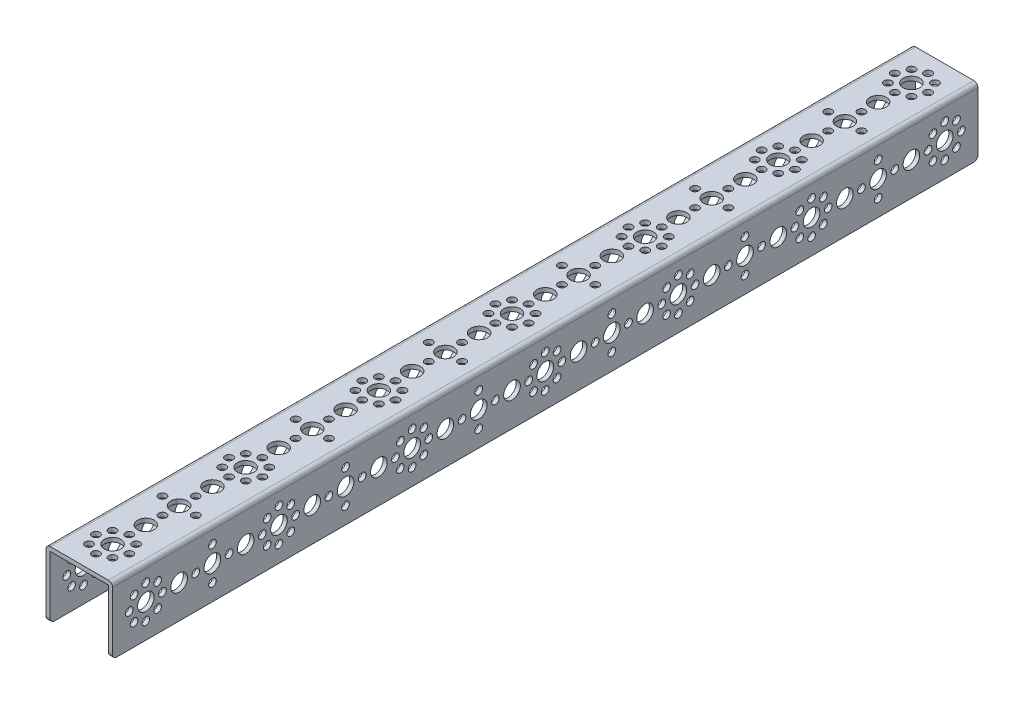
SolidWorks part; units mm, degrees
ref_plane "Front Plane" through (0, 0, 0) normal (0, 0, 1) x (1, 0, 0)
ref_plane "Top Plane" through (0, 0, 0) normal (0, 1, 0) x (1, 0, 0)
ref_plane "Right Plane" through (0, 0, 0) normal (1, 0, 0) x (0, 0, -1)
ref_plane "Plane1" through (-16, 0, 0) normal (-1, 0, 0) x (0, -1, 0)
sketch "Sketch1" plane through (-16, 0, 0) normal (-1, 0, 0) x (0, -1, 0)
  line L0 (16, 0) -> (-16, 0)
  line L1 (-16, 0) -> (-16, -416)
  line L2 (-16, -416) -> (16, -416)
  line L3 (16, -416) -> (16, 0)
extrude "Boss-Extrude1" add sketch "Sketch1" against normal blind 32
sketch "Sketch2" plane through (0, 0, 0) normal (0, 0, 1) x (1, 0, 0)
  line L0 (-14, -16) -> (14, -16)
  line L1 (14, -16) -> (14, 14)
  line L2 (14, 14) -> (-14, 14)
  line L3 (-14, 14) -> (-14, -16)
extrude "Cut-Extrude1" cut sketch "Sketch2" against normal through all
hole_wizard "Ø8.0 (8) Diameter Hole1" positions "Sketch4" profile "Sketch3" hole size "Ø8.0" standard "ANSI Metric"
sketch "Sketch4" plane through (14, 0, 0) normal (-1, 0, 0) x (0, 0, 1)
  point P0 (-80, 0)
  point P1 (-112, 0)
  point P2 (-16, 0)
  point P3 (-48, 0)
  point P4 (-128, 0)
  point P5 (-96, 0.1754)
  point P6 (-64, 0)
  point P7 (-32, 0)
  point P8 (-272, 0)
  point P9 (-336, 0)
  point P10 (-304, 0)
  point P11 (-400, 0)
  point P12 (-368, 0)
  point P13 (-288, 0)
  point P14 (-320, -0.1754)
  point P15 (-352, 0)
  point P16 (-384, 0)
  point P17 (-208, 0)
  point P18 (-240, 0)
  point P19 (-144, 0)
  point P20 (-176, 0)
  point P21 (-256, 0)
  point P22 (-224, 0.1754)
  point P23 (-192, 0)
  point P24 (-160, 0)
sketch "Sketch3" plane through (14, 0, -80) normal (0, 1, 0) x (0, 0, 1)
  line L0 (0, 0) -> (0, 2)
  line L1 (0, 2) -> (4, 2)
  line L2 (4, 2) -> (4, 0)
  line L5 (4, 0) -> (0, 0)
  line L11 (0, -6.35) -> (0, 107.95) construction
  dimension "Thru Hole Dia." = 8
  dimension "Thru Hole Depth" = 2
hole_wizard "Ø3.7 (3.7) Diameter Hole1" positions "Sketch6" profile "Sketch5" hole size "Ø3.7" standard "ANSI Metric"
sketch "Sketch6" plane through (14, 0, 0) normal (-1, 0, 0) x (0, 0, 1)
  point P0 (-74.34, -5.66)
  point P1 (-85.66, -5.66)
  point P2 (-85.66, 5.66)
  point P3 (-74.34, 5.66)
  point P4 (-80, 8)
  point P5 (-80, -8)
  point P6 (-72, 0)
  point P7 (-88, 0)
  point P8 (-112, 8)
  point P9 (-112, -8)
  point P10 (-104, 0)
  point P11 (-120, 0)
  point P12 (-21.66, -5.66)
  point P13 (-21.66, 5.66)
  point P14 (-8, 0)
  point P15 (-10.34, -5.66)
  point P16 (-10.34, 5.66)
  point P17 (-16, 8)
  point P18 (-48, 8)
  point P19 (-48, -8)
  point P20 (-40, 0)
  point P21 (-56, 0)
  point P22 (-16, -8)
  point P23 (-24, 0)
  point P24 (-277.66, -5.66)
  point P25 (-277.66, 5.66)
  point P26 (-264, 0)
  point P27 (-266.34, -5.66)
  point P28 (-266.34, 5.66)
  point P29 (-272, 8)
  point P30 (-272, -8)
  point P31 (-280, 0)
  point P32 (-341.66, 5.66)
  point P33 (-330.34, 5.66)
  point P34 (-330.34, -5.66)
  point P35 (-341.66, -5.66)
  point P36 (-336, -8)
  point P37 (-336, 8)
  point P38 (-344, 0)
  point P39 (-328, 0)
  point P40 (-304, -8)
  point P41 (-304, 8)
  point P42 (-312, 0)
  point P43 (-296, 0)
  point P44 (-405.66, 5.66)
  point P45 (-394.34, 5.66)
  point P46 (-394.34, -5.66)
  point P47 (-405.66, -5.66)
  point P48 (-400, -8)
  point P49 (-400, 8)
  point P50 (-408, 0)
  point P51 (-392, 0)
  point P52 (-368, -8)
  point P53 (-368, 8)
  point P54 (-376, 0)
  point P55 (-360, 0)
  point P56 (-202.34, -5.66)
  point P57 (-213.66, -5.66)
  point P58 (-213.66, 5.66)
  point P59 (-202.34, 5.66)
  point P60 (-208, 8)
  point P61 (-208, -8)
  point P62 (-200, 0)
  point P63 (-216, 0)
  point P64 (-240, 8)
  point P65 (-240, -8)
  point P66 (-232, 0)
  point P67 (-248, 0)
  point P68 (-149.66, -5.66)
  point P69 (-149.66, 5.66)
  point P70 (-136, 0)
  point P71 (-138.34, -5.66)
  point P72 (-138.34, 5.66)
  point P73 (-144, 8)
  point P74 (-176, 8)
  point P75 (-176, -8)
  point P76 (-168, 0)
  point P77 (-184, 0)
  point P78 (-144, -8)
  point P79 (-152, 0)
sketch "Sketch5" plane through (14, -5.66, -74.34) normal (0, 1, 0) x (0, 0, 1)
  line L0 (0, 0) -> (0, 2)
  line L1 (0, 2) -> (1.85, 2)
  line L2 (1.85, 2) -> (1.85, 0)
  line L5 (1.85, 0) -> (0, 0)
  line L11 (0, -6.35) -> (0, 107.95) construction
  dimension "Thru Hole Dia." = 3.7
  dimension "Thru Hole Depth" = 2
hole_wizard "Ø8.0 (8) Diameter Hole2" positions "Sketch8" profile "Sketch7" hole size "Ø8.0" standard "ANSI Metric"
sketch "Sketch8" plane through (0, 14, 0) normal (0, -1, 0) x (-1, 0, 0)
  point P0 (0, 336)
  point P1 (0, 304)
  point P2 (0, 400)
  point P3 (0, 368)
  point P4 (0, 288)
  point P5 (-0.1754, 320)
  point P6 (0, 352)
  point P7 (0, 384)
  point P8 (0, 144)
  point P9 (0, 80)
  point P10 (0, 112)
  point P11 (0, 16)
  point P12 (0, 48)
  point P13 (0, 128)
  point P14 (0.1754, 96)
  point P15 (0, 64)
  point P16 (0, 32)
  point P17 (0, 208)
  point P18 (0, 176)
  point P19 (0, 272)
  point P20 (0, 240)
  point P21 (0, 160)
  point P22 (-0.1754, 192)
  point P23 (0, 224)
  point P24 (0, 256)
sketch "Sketch7" plane through (0, 14, -336) normal (1, 0, 0) x (0, 0, -1)
  line L0 (0, 0) -> (0, 2)
  line L1 (0, 2) -> (4, 2)
  line L2 (4, 2) -> (4, 0)
  line L5 (4, 0) -> (0, 0)
  line L11 (0, -6.35) -> (0, 107.95) construction
  dimension "Thru Hole Dia." = 8
  dimension "Thru Hole Depth" = 2
hole_wizard "Ø3.7 (3.7) Diameter Hole2" positions "Sketch10" profile "Sketch9" hole size "Ø3.7" standard "ANSI Metric"
sketch "Sketch10" plane through (0, 14, 0) normal (0, -1, 0) x (-1, 0, 0)
  point P0 (5.66, 341.66)
  point P1 (5.66, 330.34)
  point P2 (-5.66, 330.34)
  point P3 (-5.66, 341.66)
  point P4 (-8, 336)
  point P5 (8, 336)
  point P6 (0, 344)
  point P7 (0, 328)
  point P8 (-8, 304)
  point P9 (8, 304)
  point P10 (0, 312)
  point P11 (0, 296)
  point P12 (5.66, 394.34)
  point P13 (-5.66, 394.34)
  point P14 (0, 408)
  point P15 (5.66, 405.66)
  point P16 (-5.66, 405.66)
  point P17 (-8, 400)
  point P18 (-8, 368)
  point P19 (8, 368)
  point P20 (0, 376)
  point P21 (0, 360)
  point P22 (8, 400)
  point P23 (0, 392)
  point P24 (5.66, 138.34)
  point P25 (-5.66, 138.34)
  point P26 (0, 152)
  point P27 (5.66, 149.66)
  point P28 (-5.66, 149.66)
  point P29 (-8, 144)
  point P30 (8, 144)
  point P31 (0, 136)
  point P32 (-5.66, 74.34)
  point P33 (-5.66, 85.66)
  point P34 (5.66, 85.66)
  point P35 (5.66, 74.34)
  point P36 (8, 80)
  point P37 (-8, 80)
  point P38 (0, 72)
  point P39 (0, 88)
  point P40 (8, 112)
  point P41 (-8, 112)
  point P42 (0, 104)
  point P43 (0, 120)
  point P44 (-5.66, 10.34)
  point P45 (-5.66, 21.66)
  point P46 (5.66, 21.66)
  point P47 (5.66, 10.34)
  point P48 (8, 16)
  point P49 (-8, 16)
  point P50 (0, 8)
  point P51 (0, 24)
  point P52 (8, 48)
  point P53 (-8, 48)
  point P54 (0, 40)
  point P55 (0, 56)
  point P56 (5.66, 213.66)
  point P57 (5.66, 202.34)
  point P58 (-5.66, 202.34)
  point P59 (-5.66, 213.66)
  point P60 (-8, 208)
  point P61 (8, 208)
  point P62 (0, 216)
  point P63 (0, 200)
  point P64 (-8, 176)
  point P65 (8, 176)
  point P66 (0, 184)
  point P67 (0, 168)
  point P68 (5.66, 266.34)
  point P69 (-5.66, 266.34)
  point P70 (0, 280)
  point P71 (5.66, 277.66)
  point P72 (-5.66, 277.66)
  point P73 (-8, 272)
  point P74 (-8, 240)
  point P75 (8, 240)
  point P76 (0, 248)
  point P77 (0, 232)
  point P78 (8, 272)
  point P79 (0, 264)
sketch "Sketch9" plane through (-5.66, 14, -341.66) normal (1, 0, 0) x (0, 0, -1)
  line L0 (0, 0) -> (0, 2)
  line L1 (0, 2) -> (1.85, 2)
  line L2 (1.85, 2) -> (1.85, 0)
  line L5 (1.85, 0) -> (0, 0)
  line L11 (0, -6.35) -> (0, 107.95) construction
  dimension "Thru Hole Dia." = 3.7
  dimension "Thru Hole Depth" = 2
hole_wizard "Ø8.0 (8) Diameter Hole3" positions "Sketch12" profile "Sketch11" hole size "Ø8.0" standard "ANSI Metric"
sketch "Sketch12" plane through (-16, 0, 0) normal (-1, 0, 0) x (0, 0, 1)
  point P0 (-80, 0)
  point P1 (-112, 0)
  point P2 (-16, 0)
  point P3 (-48, 0)
  point P4 (-128, 0)
  point P5 (-96, 0.1754)
  point P6 (-64, 0)
  point P7 (-32, 0)
  point P8 (-272, 0)
  point P9 (-336, 0)
  point P10 (-304, 0)
  point P11 (-400, 0)
  point P12 (-368, 0)
  point P13 (-288, 0)
  point P14 (-320, -0.1754)
  point P15 (-352, 0)
  point P16 (-384, 0)
  point P17 (-208, 0)
  point P18 (-240, 0)
  point P19 (-144, 0)
  point P20 (-176, 0)
  point P21 (-256, 0)
  point P22 (-224, 0.1754)
  point P23 (-192, 0)
  point P24 (-160, 0)
sketch "Sketch11" plane through (-16, 0, -80) normal (0, 1, 0) x (0, 0, 1)
  line L0 (0, 0) -> (0, 32)
  line L1 (0, 32) -> (4, 32)
  line L2 (4, 32) -> (4, 0)
  line L5 (4, 0) -> (0, 0)
  line L11 (0, -6.35) -> (0, 107.95) construction
  dimension "Thru Hole Dia." = 8
  dimension "Thru Hole Depth" = 32
hole_wizard "Ø3.7 (3.7) Diameter Hole3" positions "Sketch14" profile "Sketch13" hole size "Ø3.7" standard "ANSI Metric"
sketch "Sketch14" plane through (-16, 0, 0) normal (-1, 0, 0) x (0, 0, 1)
  point P0 (-74.34, -5.66)
  point P1 (-85.66, -5.66)
  point P2 (-85.66, 5.66)
  point P3 (-74.34, 5.66)
  point P4 (-80, 8)
  point P5 (-80, -8)
  point P6 (-72, 0)
  point P7 (-88, 0)
  point P8 (-112, 8)
  point P9 (-112, -8)
  point P10 (-104, 0)
  point P11 (-120, 0)
  point P12 (-21.66, -5.66)
  point P13 (-21.66, 5.66)
  point P14 (-8, 0)
  point P15 (-10.34, -5.66)
  point P16 (-10.34, 5.66)
  point P17 (-16, 8)
  point P18 (-48, 8)
  point P19 (-48, -8)
  point P20 (-40, 0)
  point P21 (-56, 0)
  point P22 (-16, -8)
  point P23 (-24, 0)
  point P24 (-277.66, -5.66)
  point P25 (-277.66, 5.66)
  point P26 (-264, 0)
  point P27 (-266.34, -5.66)
  point P28 (-266.34, 5.66)
  point P29 (-272, 8)
  point P30 (-272, -8)
  point P31 (-280, 0)
  point P32 (-341.66, 5.66)
  point P33 (-330.34, 5.66)
  point P34 (-330.34, -5.66)
  point P35 (-341.66, -5.66)
  point P36 (-336, -8)
  point P37 (-336, 8)
  point P38 (-344, 0)
  point P39 (-328, 0)
  point P40 (-304, -8)
  point P41 (-304, 8)
  point P42 (-312, 0)
  point P43 (-296, 0)
  point P44 (-405.66, 5.66)
  point P45 (-394.34, 5.66)
  point P46 (-394.34, -5.66)
  point P47 (-405.66, -5.66)
  point P48 (-400, -8)
  point P49 (-400, 8)
  point P50 (-408, 0)
  point P51 (-392, 0)
  point P52 (-368, -8)
  point P53 (-368, 8)
  point P54 (-376, 0)
  point P55 (-360, 0)
  point P56 (-202.34, -5.66)
  point P57 (-213.66, -5.66)
  point P58 (-213.66, 5.66)
  point P59 (-202.34, 5.66)
  point P60 (-208, 8)
  point P61 (-208, -8)
  point P62 (-200, 0)
  point P63 (-216, 0)
  point P64 (-240, 8)
  point P65 (-240, -8)
  point P66 (-232, 0)
  point P67 (-248, 0)
  point P68 (-149.66, -5.66)
  point P69 (-149.66, 5.66)
  point P70 (-136, 0)
  point P71 (-138.34, -5.66)
  point P72 (-138.34, 5.66)
  point P73 (-144, 8)
  point P74 (-176, 8)
  point P75 (-176, -8)
  point P76 (-168, 0)
  point P77 (-184, 0)
  point P78 (-144, -8)
  point P79 (-152, 0)
sketch "Sketch13" plane through (-16, -5.66, -74.34) normal (0, 1, 0) x (0, 0, 1)
  line L0 (0, 0) -> (0, 32)
  line L1 (0, 32) -> (1.85, 32)
  line L2 (1.85, 32) -> (1.85, 0)
  line L5 (1.85, 0) -> (0, 0)
  line L11 (0, -6.35) -> (0, 107.95) construction
  dimension "Thru Hole Dia." = 3.7
  dimension "Thru Hole Depth" = 32
fillet "Fillet1" radius 2 6 edges at (15, -16, -416) (15, -16, 0) (16, 16, -208) (-15, -16, 0) (-15, -16, -416) (-16, 16, -208)
